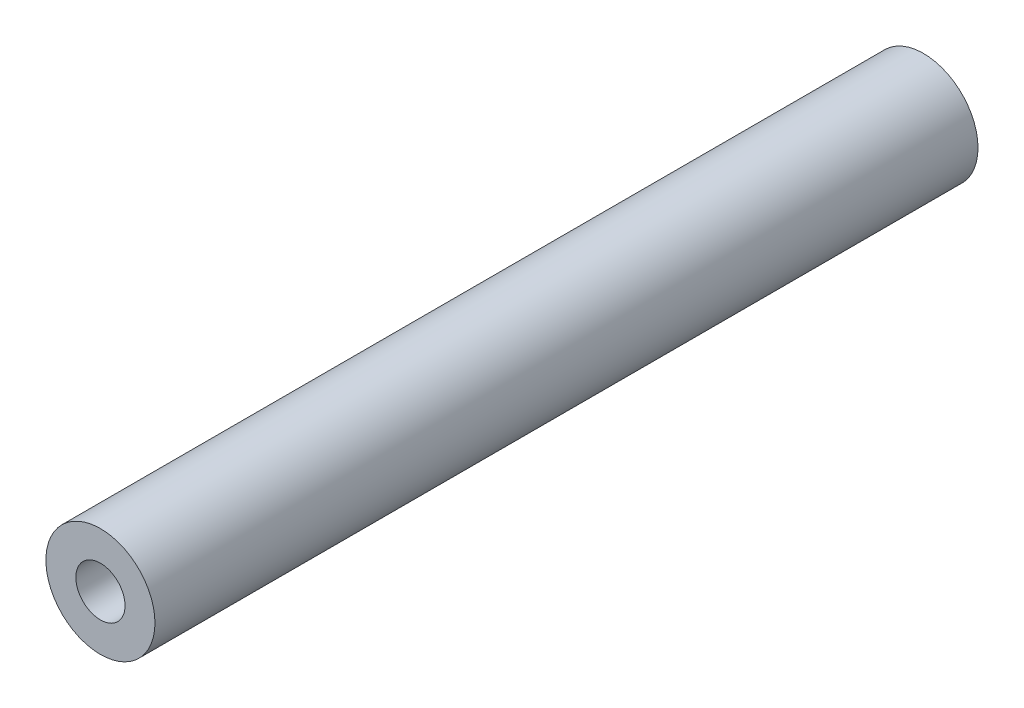
SolidWorks part; units mm, degrees
material "1060 Alloy"
ref_plane "Front Plane" through (0, 0, 0) normal (0, 0, 1) x (1, 0, 0)
ref_plane "Top Plane" through (0, 0, 0) normal (0, 1, 0) x (1, 0, 0)
ref_plane "Right Plane" through (0, 0, 0) normal (1, 0, 0) x (0, 0, -1)
sketch "Sketch1" plane through (0, 0, 0) normal (0, 0, 1) x (1, 0, 0)
  circle A0 centre (0, 0) radius 3
  dimension "D1" = 6
extrude "Boss-Extrude1" add sketch "Sketch1" along normal blind 45.28
hole_wizard "#6-32 Tapped Hole1" positions "Sketch2" profile "Sketch3" tap size "#6-32" standard "ANSI Inch"
sketch "Sketch2" plane through (0, 0, 45.28) normal (0, 0, 1) x (1, 0, 0)
  point P0 (0, 0)
sketch "Sketch3" plane through (0, 0, 45.28) normal (1, 0, 0) x (0, -1, 0)
  line L0 (0, 0) -> (0, 10.8127)
  line L1 (0, 10.8127) -> (1.3525, 10)
  line L2 (1.3525, 10) -> (1.3525, 0)
  line L5 (1.3525, 0) -> (0, 0)
  line L10 (0, 10.8127) -> (-1.3525, 10) construction
  line L11 (0, -6.35) -> (0, 107.95) construction
  dimension "Tap Drill Dia." = 2.7051
  dimension "Tap Drill Depth" = 10
  dimension "Drill Angle" = 118
cosmetic thread "Hole Thread1" parameters "D1"=7.01, "D2"=3.5052
hole_wizard "#6-32 Tapped Hole2" positions "Sketch4" profile "Sketch5" tap size "#6-32" standard "ANSI Inch"
sketch "Sketch4" plane through (0, 0, 0) normal (0, 0, -1) x (-1, 0, 0)
  point P0 (0, 0)
sketch "Sketch5" plane through (0, 0, 0) normal (1, 0, 0) x (0, 1, 0)
  line L0 (0, 0) -> (0, 10.8127)
  line L1 (0, 10.8127) -> (1.3525, 10)
  line L2 (1.3525, 10) -> (1.3525, 0)
  line L5 (1.3525, 0) -> (0, 0)
  line L10 (0, 10.8127) -> (-1.3525, 10) construction
  line L11 (0, -6.35) -> (0, 107.95) construction
  dimension "Tap Drill Dia." = 2.7051
  dimension "Tap Drill Depth" = 10
  dimension "Drill Angle" = 118
cosmetic thread "Hole Thread2"
